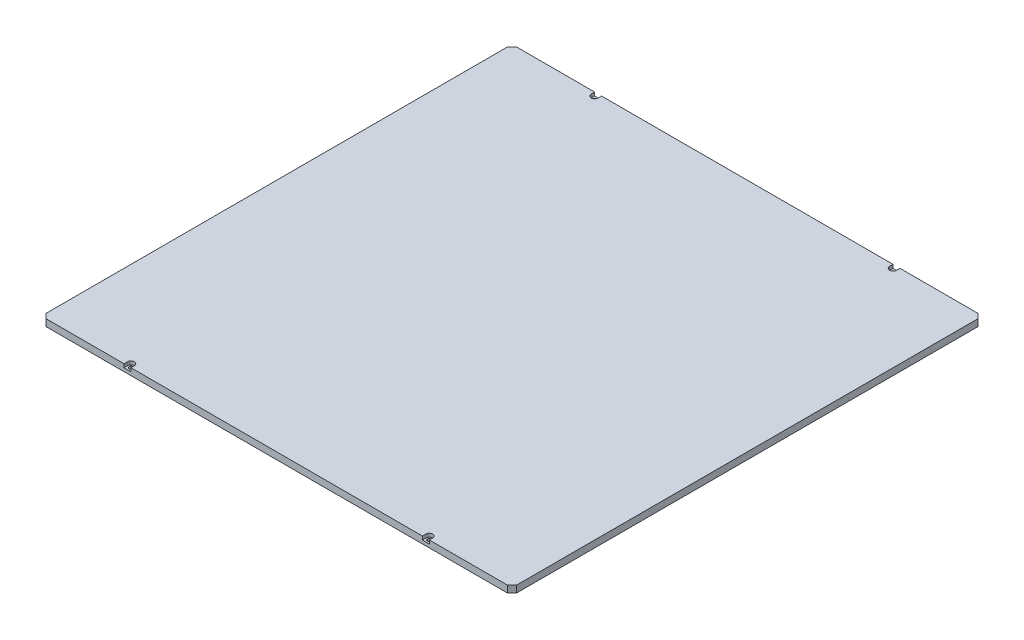
SolidWorks part; units mm, degrees
ref_plane "Frente" through (0, 0, 0) normal (0, 0, 1) x (1, 0, 0)
ref_plane "Topo" through (0, 0, 0) normal (0, 1, 0) x (1, 0, 0)
ref_plane "Lateral" through (0, 0, 0) normal (1, 0, 0) x (0, 0, -1)
sketch "Sketch1" plane through (0, 0, 0) normal (0, 1, 0) x (1, 0, 0)
  line L1 (205, -205) -> (-205, -205)
  line L2 (205, -205) -> (205, 205)
  line L3 (205, 205) -> (-205, 205)
  line L4 (-205, -205) -> (-205, 205)
  line L5 (0, 205) -> (0, -205) construction
  line L6 (205, 0) -> (-205, 0) construction
  point P0 (0, 0)
  dimension "D1" = 410
  dimension "D2" = 410
extrude "Boss-Extrude1" add sketch "Sketch1" along normal mid plane 6
chamfer "Chamfer1" distance 4 angle 45 4 edges at (-205, 0, -205) (205, 0, -205) (205, 0, 205) (-205, 0, 205)
sketch "Sketch2" plane through (0, 3, 0) normal (0, 1, 0) x (1, 0, 0)
  line L0 (201, 205) -> (-201, 205) construction
  line L1 (-130, 202) -> (130, 202) construction
  line L2 (-130, 202) -> (-130, -202) construction
  line L3 (-130, -202) -> (130, -202) construction
  line L4 (130, 202) -> (130, -202) construction
  line L5 (-201, -205) -> (201, -205) construction
  line L6 (-205, 201) -> (-205, -201) construction
  line L7 (0, 202) -> (0, 0) construction
  line L8 (-133, 202) -> (-133, 205)
  line L9 (-133, 205) -> (-127, 205)
  line L10 (-127, 205) -> (-127, 202)
  line L11 (127, 202) -> (127, 205)
  line L12 (127, 205) -> (133, 205)
  line L13 (133, 205) -> (133, 202)
  line L14 (0, 0) -> (-130, 0) construction
  line L15 (-133, -202) -> (-133, -205)
  line L16 (-133, -205) -> (-127, -205)
  line L17 (-127, -205) -> (-127, -202)
  line L18 (127, -202) -> (127, -205)
  line L19 (127, -205) -> (133, -205)
  line L20 (133, -205) -> (133, -202)
  arc A0 (133, -202) -> (127, -202) centre (130, -202) ccw
  arc A1 (-127, -202) -> (-133, -202) centre (-130, -202) ccw
  arc A2 (-133, 202) -> (-127, 202) centre (-130, 202) ccw
  arc A3 (127, 202) -> (133, 202) centre (130, 202) ccw
  point P8 (0, -205)
  dimension "D1" = 6
  dimension "D2" = 3
  dimension "D4" = 75
extrude "Cut-Extrude1" cut sketch "Sketch2" against normal blind 3
sketch "Sketch3" plane through (0, 0, 0) normal (0, 1, 0) x (1, 0, 0)
  circle A0 centre (-130, -202) radius 1.65
  circle A1 centre (130, -202) radius 1.65
  circle A2 centre (130, 202) radius 1.65
  circle A3 centre (-130, 202) radius 1.65
  dimension "D1" = 3.3
extrude "Cut-Extrude2" cut sketch "Sketch3" against normal through all
